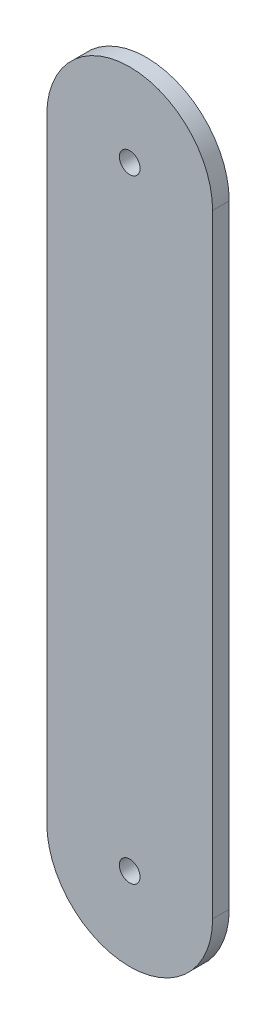
SolidWorks part; units mm, degrees
material "自訂玻璃纖維"
ref_plane "前基準面" through (0, 0, 0) normal (0, 0, 1) x (1, 0, 0)
ref_plane "上基準面" through (0, 0, 0) normal (0, 1, 0) x (1, 0, 0)
ref_plane "右基準面" through (0, 0, 0) normal (1, 0, 0) x (0, 0, -1)
sketch "草圖1" plane through (0, 0, 0) normal (0, 0, 1) x (1, 0, 0)
  line L2 (-28.6834, 42.2568) -> (-28.6834, -31.7432)
  line L4 (-8.6834, 42.2568) -> (-8.6834, -31.7432)
  arc A0 (-8.6834, 42.2568) -> (-28.6834, 42.2568) centre (-18.6834, 42.2568) ccw
  arc A1 (-8.6834, -31.7432) -> (-28.6834, -31.7432) centre (-18.6834, -31.7432) cw
  circle A2 centre (-18.6834, 42.2568) radius 1.25
  circle A3 centre (-18.6834, -31.7432) radius 1.25
  point P4 (-18.6834, 42.2568)
  point P5 (-18.6834, -31.7432)
  dimension "D1" = 2.5
  dimension "D2" = 2.5
  dimension "D3" = 10
  dimension "D4" = 74
  dimension "D6" = 0
  dimension "D5" = 74
extrude "填料-伸長1" add sketch "草圖1" along normal blind 2
